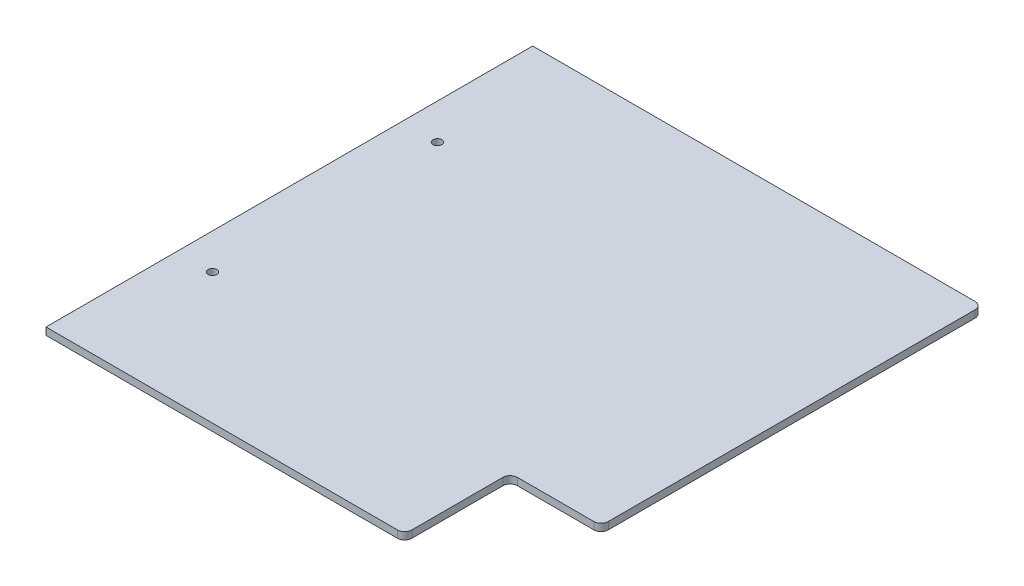
SolidWorks part; units mm, degrees
ref_plane "Alzado" through (0, 0, 0) normal (0, 0, 1) x (1, 0, 0)
ref_plane "Planta" through (0, 0, 0) normal (0, 1, 0) x (1, 0, 0)
ref_plane "Vista lateral" through (0, 0, 0) normal (1, 0, 0) x (0, 0, -1)
sketch "Croquis1" plane through (0, 0, 0) normal (0, 1, 0) x (1, 0, 0)
  line L6 (-117.7768, -199.572) -> (-117.7768, 134.928)
  line L7 (-117.7768, 134.928) -> (191.2232, 134.928)
  line L8 (191.2232, -127.072) -> (191.2232, 134.928)
  line L11 (-117.7768, -199.572) -> (128.7232, -199.572)
  line L19 (191.2232, -127.072) -> (128.7232, -127.072)
  line L22 (128.7232, -127.072) -> (128.7232, -199.572)
  circle A0 centre (-93.2768, 44.928) radius 3
  circle A1 centre (-93.2768, -109.572) radius 3
  dimension "D3" = 262
  dimension "D4" = 246.5
  dimension "D5" = 6
  dimension "D6" = 6
  dimension "D7" = 90
  dimension "D8" = 90
  dimension "D1" = 62.5
  dimension "D2" = 72.5
  dimension "D9" = 24.5
extrude "Saliente-Extruir1" add sketch "Croquis1" along normal blind 5
fillet "Redondeo1" radius 5 4 edges at (128.7232, 2.5, 199.572) (128.7232, 2.5, 127.072) (191.2232, 2.5, 127.072) (191.2232, 2.5, -134.928)
